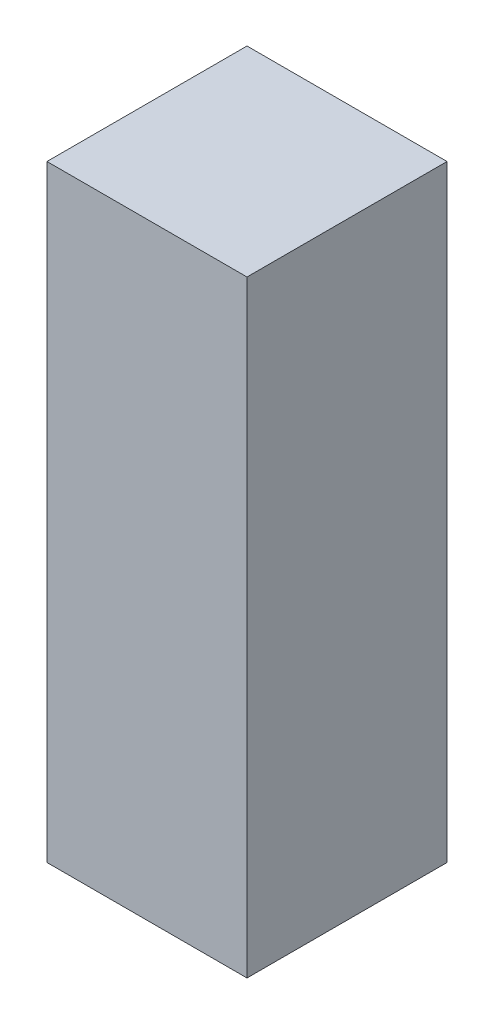
SolidWorks part; units mm, degrees
ref_plane "Front Plane" through (0, 0, 0) normal (0, 0, 1) x (1, 0, 0)
ref_plane "Top Plane" through (0, 0, 0) normal (0, 1, 0) x (1, 0, 0)
ref_plane "Right Plane" through (0, 0, 0) normal (1, 0, 0) x (0, 0, -1)
sketch "Sketch1" plane through (0, 0, 0) normal (0, 1, 0) x (1, 0, 0)
  line L1 (-50, -50) -> (50, -50)
  line L2 (-50, -50) -> (-50, 50)
  line L3 (-50, 50) -> (50, 50)
  line L4 (50, -50) -> (50, 50)
  line L5 (-50, -50) -> (50, 50) construction
  line L6 (-50, 50) -> (50, -50) construction
  point P0 (0, 0)
  dimension "D1" = 100
  dimension "D2" = 100
extrude "Boss-Extrude1" add sketch "Sketch1" along normal blind 303.5
